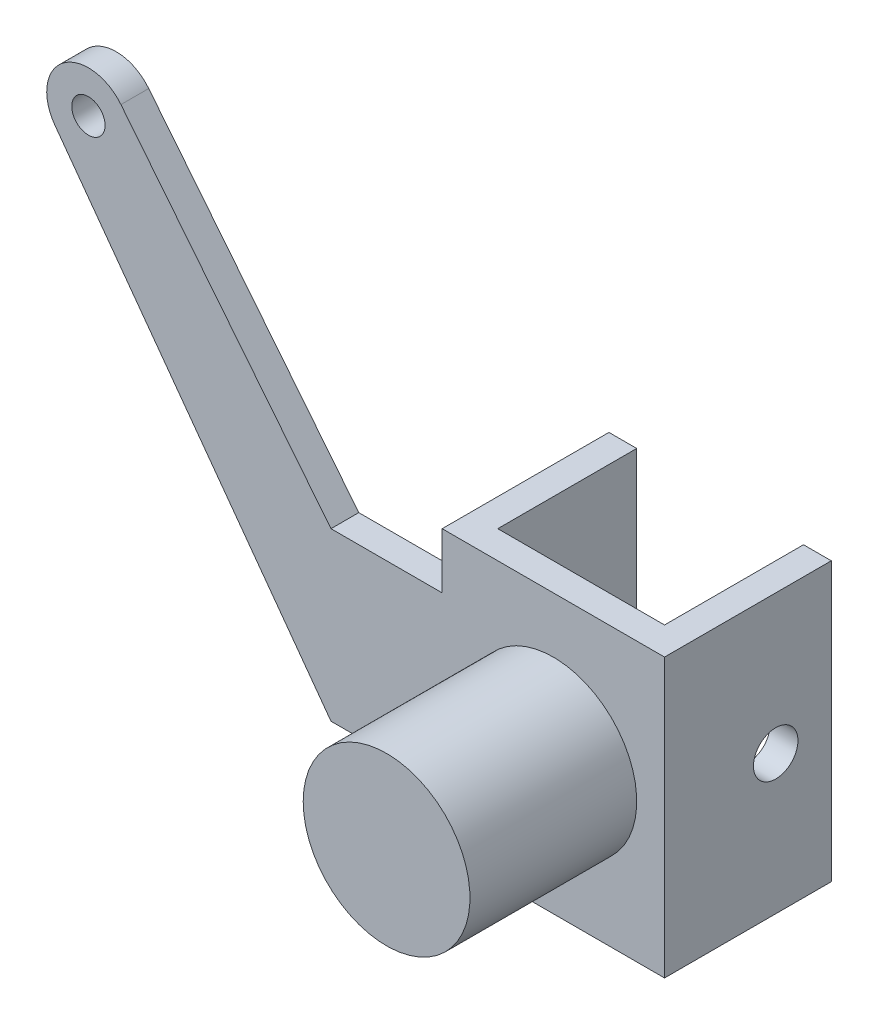
SolidWorks part; units mm, degrees
ref_plane "Front Plane" through (0, 0, 0) normal (0, 0, 1) x (1, 0, 0)
ref_plane "Top Plane" through (0, 0, 0) normal (0, 1, 0) x (1, 0, 0)
ref_plane "Right Plane" through (0, 0, 0) normal (1, 0, 0) x (0, 0, -1)
sketch "Sketch1" plane through (0, 0, 0) normal (0, 0, 1) x (1, 0, 0)
  line L1 (-20, -25) -> (20, -25)
  line L2 (-20, -25) -> (-20, 25)
  line L3 (-20, 25) -> (20, 25)
  line L4 (20, -25) -> (20, 25)
  line L5 (-20, -25) -> (20, 25) construction
  line L6 (-20, 25) -> (20, -25) construction
  point P0 (0, 0)
  dimension "D1" = 40
  dimension "D2" = 50
extrude "Boss-Extrude1" add sketch "Sketch1" along normal blind 5
sketch "Sketch2" plane through (0, 0, 5) normal (0, 0, 1) x (1, 0, 0)
  line L0 (-20, -25) -> (20, -25) construction
  line L1 (-20, 25) -> (-15, 25)
  line L2 (-20, 25) -> (-20, -25)
  line L3 (-20, -25) -> (-15, -25)
  line L4 (-15, 25) -> (-15, -25)
  line L6 (20, 25) -> (15, 25)
  line L7 (20, 25) -> (20, -25)
  line L8 (20, -25) -> (15, -25)
  line L9 (15, 25) -> (15, -25)
  dimension "D1" = 5
  dimension "D2" = 5
extrude "Boss-Extrude2" add sketch "Sketch2" along normal blind 25
sketch "Sketch3" plane through (-20, 0, 0) normal (-1, 0, 0) x (0, 0, 1)
  line L0 (15, 25) -> (15, -25) construction
  line L1 (30, 25) -> (0, 25) construction
  line L2 (30, -25) -> (0, -25) construction
  line L3 (0, 0) -> (30, 0) construction
  line L4 (30, 25) -> (30, -25) construction
  circle A0 centre (20, 0) radius 4
  dimension "D1" = 8
  dimension "D2" = 10
  dimension "D3" = 25
extrude "Cut-Extrude1" cut sketch "Sketch3" against normal through all
sketch "Sketch4" plane through (-20, 0, 0) normal (-1, 0, 0) x (0, 0, 1)
  line L0 (0, 0) -> (30, 0) construction
  line L2 (30, 25) -> (30, -25) construction
  line L3 (0, 25) -> (0, -25) construction
  line L4 (5, -15) -> (0, -15)
  line L5 (5, -15) -> (5, 15)
  line L6 (5, 15) -> (0, 15)
  line L7 (0, -15) -> (0, 15)
  line L8 (5, -15) -> (0, 15) construction
  line L9 (5, 15) -> (0, -15) construction
  point P4 (2.5, 0)
  dimension "D1" = 5
  dimension "D2" = 30
extrude "Boss-Extrude3" add sketch "Sketch4" along normal blind 20
ref_plane "Plane1" through (0, 0, 5) normal (0, 0, 1) x (1, 0, 0)
sketch "Sketch5" plane through (0, 0, 5) normal (0, 0, 1) x (1, 0, 0)
  line L0 (-40, 15) -> (-77.7859, 62.1794)
  line L2 (-89.6972, 53.0685) -> (-40, -15)
  line L4 (-40, 15) -> (-40, -15)
  arc A0 (-77.7859, 62.1794) -> (-89.6972, 53.0685) centre (-83.6398, 57.491) ccw
  circle A1 centre (-83.6398, 57.491) radius 3
  circle A2 centre (-83.6398, 57.491) radius 3 construction
  dimension "D3" = 6
  dimension "D4" = 7.5
extrude "Boss-Extrude4" add sketch "Sketch5" against normal blind 5
sketch "Sketch6" plane through (0, 0, 0) normal (0, 0, -1) x (-1, 0, 0)
  circle A0 centre (0, 0) radius 15
  dimension "D1" = 30
extrude "Boss-Extrude5" add sketch "Sketch6" along normal blind 30
mirror "Mirror1" about plane through (0, 0, -30) normal (0, 0, -1) of bodies 106
delete or keep bodies "Body-Delete/Keep 1" type delete bodies bodies 106
equation "\"rubberthickness\" = 0.0200m"
equation "\"D2@Sketch3\" = \"rubberthickness\"/2"
equation "\"D1@Boss-Extrude2\" = \"rubberthickness\"+0.005m"
